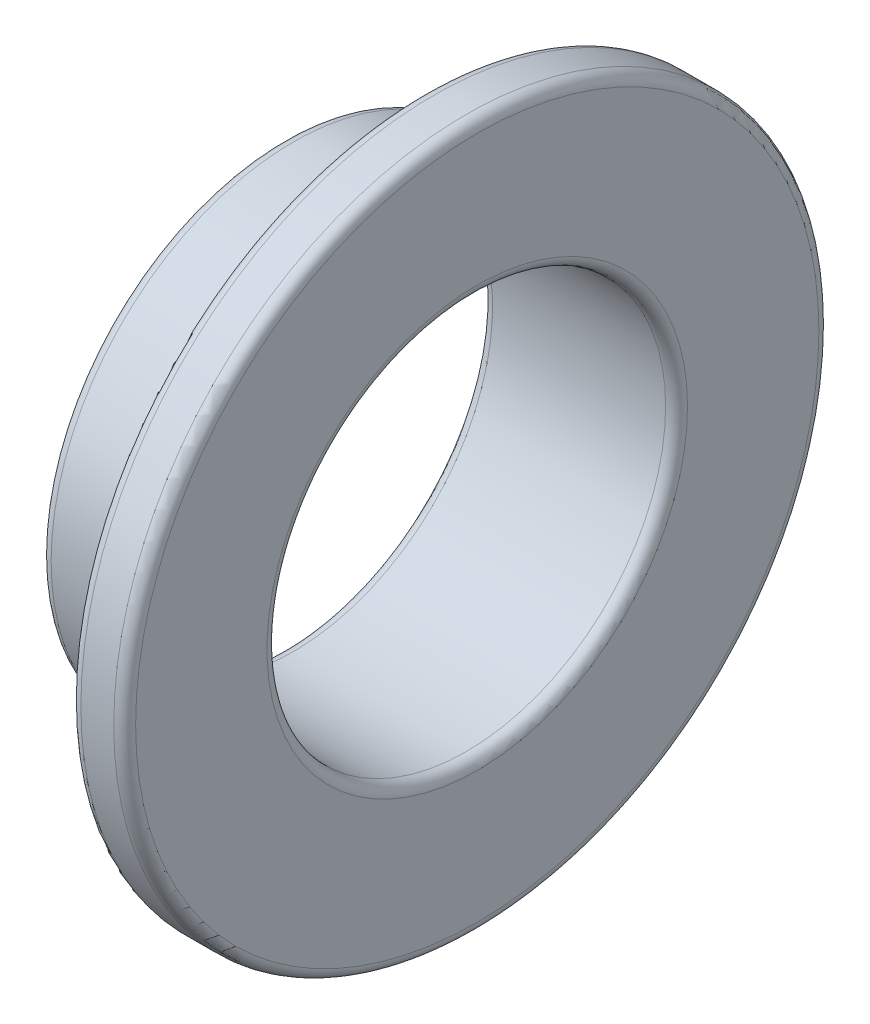
SolidWorks part; units mm, degrees
ref_plane "Front Plane" through (0, 0, 0) normal (0, 0, 1) x (1, 0, 0)
ref_plane "Top Plane" through (0, 0, 0) normal (0, 1, 0) x (1, 0, 0)
ref_plane "Right Plane" through (0, 0, 0) normal (1, 0, 0) x (0, 0, -1)
sketch "Sketch1" plane through (0, 0, 0) normal (0, 0, 1) x (1, 0, 0)
  line L0 (-30.8496, 0) -> (-13.9977, 0) construction
  line L1 (-12.5, 16.1) -> (-12.5, 9.1) construction
  line L2 (-12.5, 9.1) -> (-3.6, 9.1) construction
  line L3 (-3.6, 9.1) -> (-3.6, 11.1) construction
  line L4 (-3.6, 11.1) -> (9.96, 11.1) construction
  line L5 (9.96, 11.1) -> (9.96, 13.6) construction
  line L6 (9.96, 13.6) -> (-10, 13.6) construction
  line L7 (-10, 13.6) -> (-10, 16.1) construction
  line L8 (-10, 16.1) -> (-12.5, 16.1) construction
  line L9 (10, 16.1) -> (12.5, 16.1)
  line L10 (12.5, 16.1) -> (12.5, 9.1)
  line L11 (12.5, 9.1) -> (3.6, 9.1)
  line L12 (3.6, 9.1) -> (3.6, 11.1)
  line L13 (3.6, 11.1) -> (9.96, 11.1) construction
  line L14 (9.96, 11.1) -> (9.96, 13.6) construction
  line L15 (9.96, 13.6) -> (10, 13.6) construction
  line L16 (10, 13.6) -> (10, 16.1)
  line L17 (-3.6, 9.1) -> (3.6, 9.1) construction
  line L18 (-10, 16.1) -> (10, 16.1) construction
  line L19 (0, 0) -> (0, 9.1) construction
  line L20 (0, 16.1) -> (0, 9.1) construction
  line L21 (3.6, 11.06) -> (10, 11.06)
  line L22 (10, 11.06) -> (10, 13.6)
  dimension "D1" = 20
  dimension "D2" = 2.5
  dimension "D3" = 11.1
  dimension "D4" = 2
  dimension "D5" = 2.5
  dimension "D6" = 2.5
  dimension "D7" = 0.04
  dimension "D8" = 7.2
  dimension "D9" = 0.04
revolve "Revolve1" add sketch "Sketch1" angle 360 about L0
fillet "Fillet1" radius 0.5 6 edges at (12.5, 0, 16.1) (3.6, 0, 11.06) (10, 0, 11.06) (10, 0, 16.1) (12.5, 0, 9.1) (3.6, 0, 9.1)
